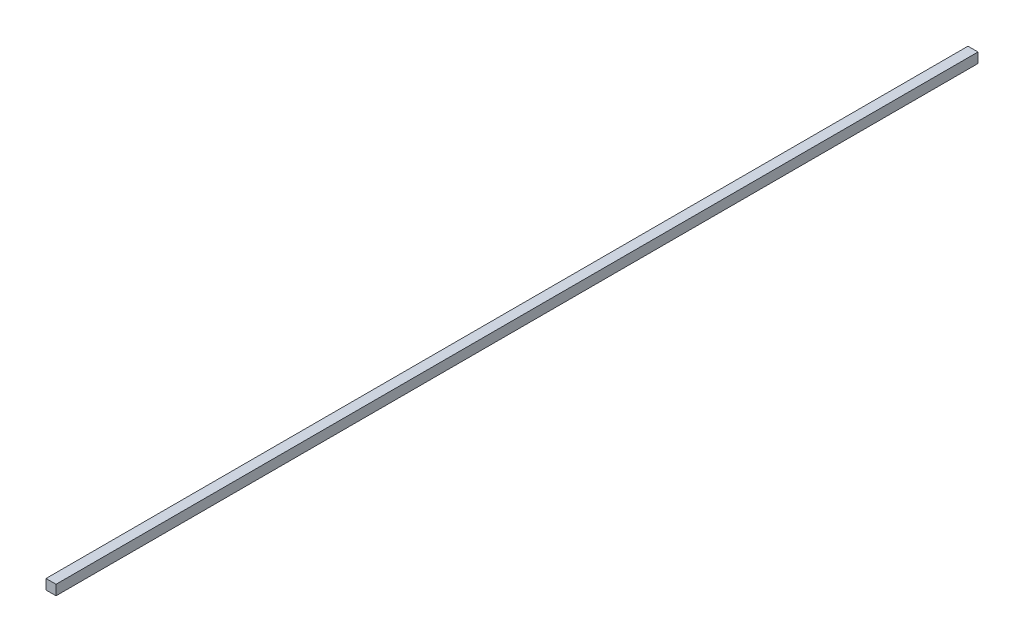
SolidWorks part; units mm, degrees
ref_plane "Front Plane" through (0, 0, 0) normal (0, 0, 1) x (1, 0, 0)
ref_plane "Top Plane" through (0, 0, 0) normal (0, 1, 0) x (1, 0, 0)
ref_plane "Right Plane" through (0, 0, 0) normal (1, 0, 0) x (0, 0, -1)
sketch "Sketch1" plane through (0, 0, 0) normal (0, 0, 1) x (1, 0, 0)
  line L1 (-12.7, 12.7) -> (12.7, 12.7)
  line L2 (-12.7, 12.7) -> (-12.7, -12.7)
  line L3 (-12.7, -12.7) -> (12.7, -12.7)
  line L4 (12.7, 12.7) -> (12.7, -12.7)
  line L5 (-12.7, 12.7) -> (12.7, -12.7) construction
  line L6 (-12.7, -12.7) -> (12.7, 12.7) construction
  point P0 (0, 0)
  dimension "D1" = 25.4
extrude "Boss-Extrude1" add sketch "Sketch1" against normal blind 2336.8
